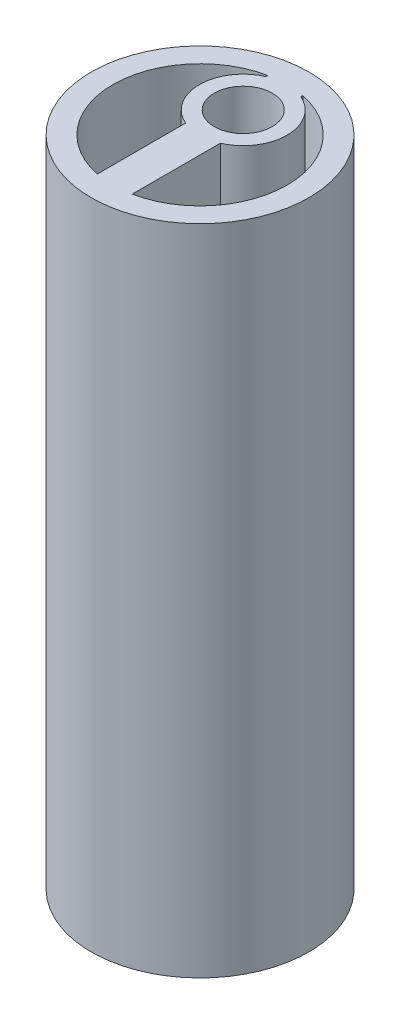
SolidWorks part; units mm, degrees
ref_plane "Front Plane" through (0, 0, 0) normal (0, 0, 1) x (1, 0, 0)
ref_plane "Top Plane" through (0, 0, 0) normal (0, 1, 0) x (1, 0, 0)
ref_plane "Right Plane" through (0, 0, 0) normal (1, 0, 0) x (0, 0, -1)
sketch "Sketch1" plane through (0, 0, 0) normal (0, 1, 0) x (1, 0, 0)
  circle A0 centre (0, 0) radius 7.5
  circle A1 centre (0, 0) radius 6
  dimension "D1" = 15
  dimension "D2" = 12
extrude "Boss-Extrude1" add sketch "Sketch1" along normal blind 45
sketch "Sketch3" plane through (0, 45, 0) normal (0, 1, 0) x (1, 0, 0)
  line L1 (-1.2, 6.7495) -> (1.2, 6.7495)
  line L2 (-1.2, 6.7495) -> (-1.2, -6.9401)
  line L3 (-1.2, -6.9401) -> (1.2, -6.9401)
  line L4 (1.2, 6.7495) -> (1.2, -6.9401)
  dimension "D1" = 1.2
  dimension "D2" = 1.2
extrude "Boss-Extrude3" add sketch "Sketch3" against normal through all
sketch "Sketch4" plane through (0, 45, 0) normal (0, 1, 0) x (1, 0, 0)
  circle A0 centre (0, 2.9749) radius 3.0196
  point P2 (0, 3.9377)
  point P3 (0, 2.9749)
extrude "Boss-Extrude4" add sketch "Sketch4" against normal through all
sketch "Sketch5" plane through (0, 45, 0) normal (0, 1, 0) x (1, 0, 0)
  circle A0 centre (0, 2.9749) radius 2
  arc A1 (1.2, 0.204) -> (1.2, 5.7459) centre (0, 2.9749) ccw construction
  dimension "D1" = 4
extrude "Cut-Extrude1" cut sketch "Sketch5" against normal through all
